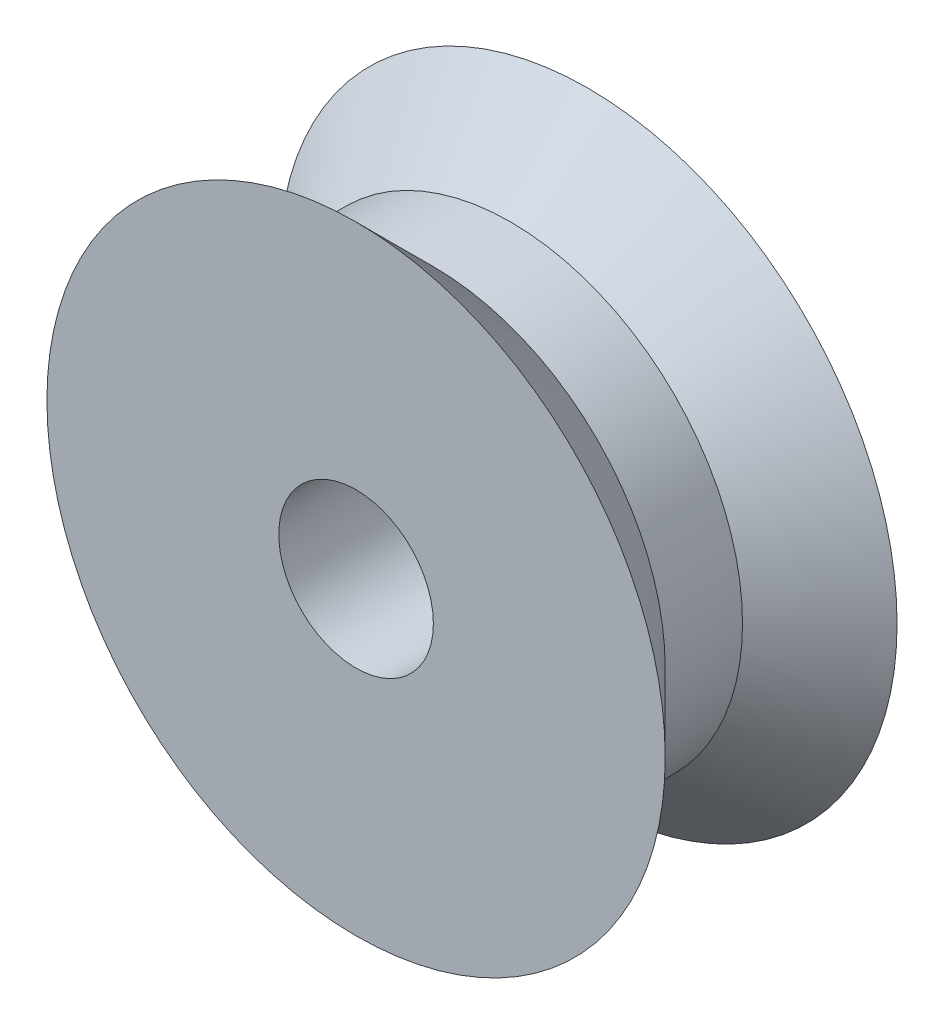
SolidWorks part; units mm, degrees
ref_plane "Front Plane" through (0, 0, 0) normal (0, 0, 1) x (1, 0, 0)
ref_plane "Top Plane" through (0, 0, 0) normal (0, 1, 0) x (1, 0, 0)
ref_plane "Right Plane" through (0, 0, 0) normal (1, 0, 0) x (0, 0, -1)
sketch "Sketch1" plane through (0, 0, 0) normal (0, 0, 1) x (1, 0, 0)
  circle A0 centre (0, 0) radius 40
  circle A1 centre (0, 0) radius 10
  dimension "D1" = 80
  dimension "D2" = 20
extrude "Boss-Extrude1" add sketch "Sketch1" along normal blind 30
sketch "Sketch2" plane through (0, 0, 0) normal (0, 1, 0) x (1, 0, 0)
  line L3 (40, -30) -> (40, 0) construction
  line L7 (40, -30) -> (40, 0)
  line L8 (0, 0) -> (0, -30) construction
  line L9 (40, 0) -> (30, -10)
  line L10 (30, -10) -> (30, -20)
  line L11 (30, -20) -> (40, -30)
  point P9 (0, -15)
  point P12 (30, -15)
  point P13 (20, 5)
  point P14 (20, -35)
  point P15 (22.9575, 7.9575)
  point P16 (0, 0)
  point P17 (16.8774, -2.9272)
  point P18 (0, 0)
  point P19 (17.8534, -27.5481)
  point P20 (0, 0)
  point P21 (0, 0)
  dimension "D1" = 10
  dimension "D2" = 45
  dimension "D3" = 45
revolve "Cut-Revolve1" cut sketch "Sketch2" angle 360 about L8
